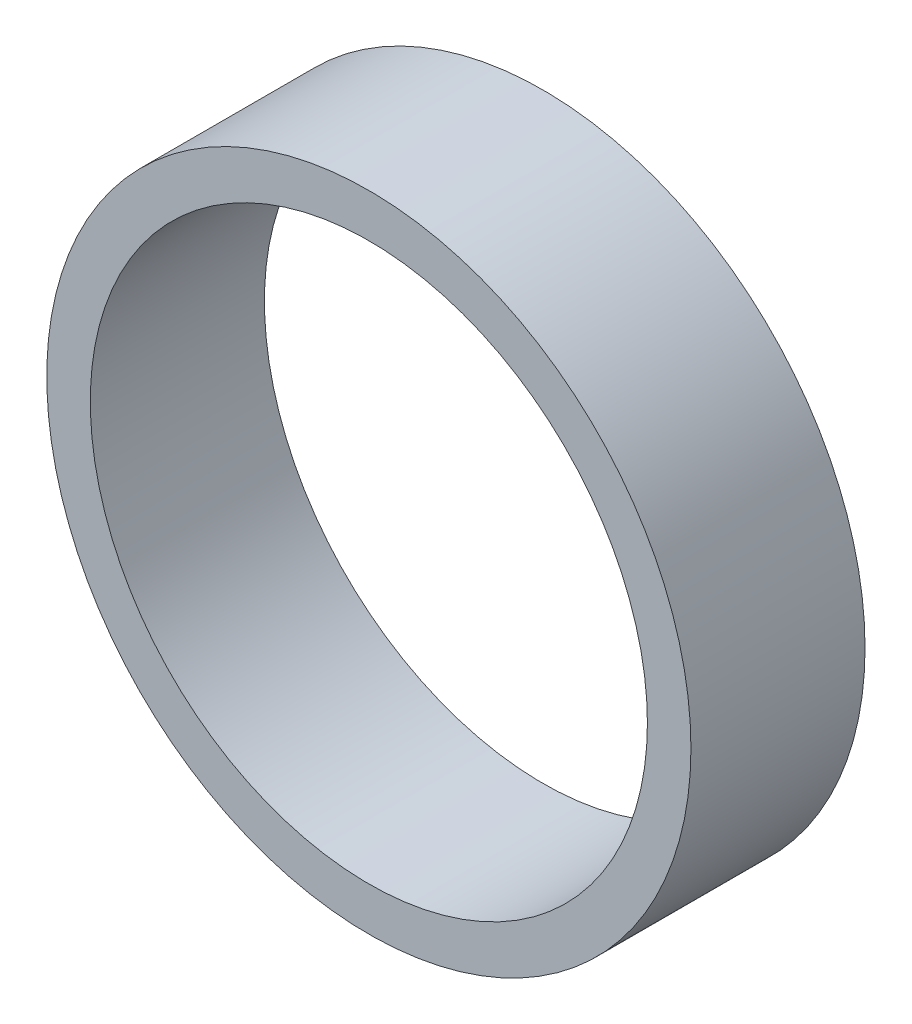
SolidWorks part; units mm, degrees
material "ABS"
ref_plane "Front Plane" through (0, 0, 0) normal (0, 0, 1) x (1, 0, 0)
ref_plane "Top Plane" through (0, 0, 0) normal (0, 1, 0) x (1, 0, 0)
ref_plane "Right Plane" through (0, 0, 0) normal (1, 0, 0) x (0, 0, -1)
sketch "Sketch1" plane through (0, 0, 5) normal (0, 0, 1) x (1, 0, 0)
  circle A0 centre (15, 0) radius 1.6
  circle A1 centre (15, 0) radius 1.85
  dimension "D1" = 3.2
  dimension "D2" = 3.7
extrude "Boss-Extrude1" add sketch "Sketch1" along normal blind 1
